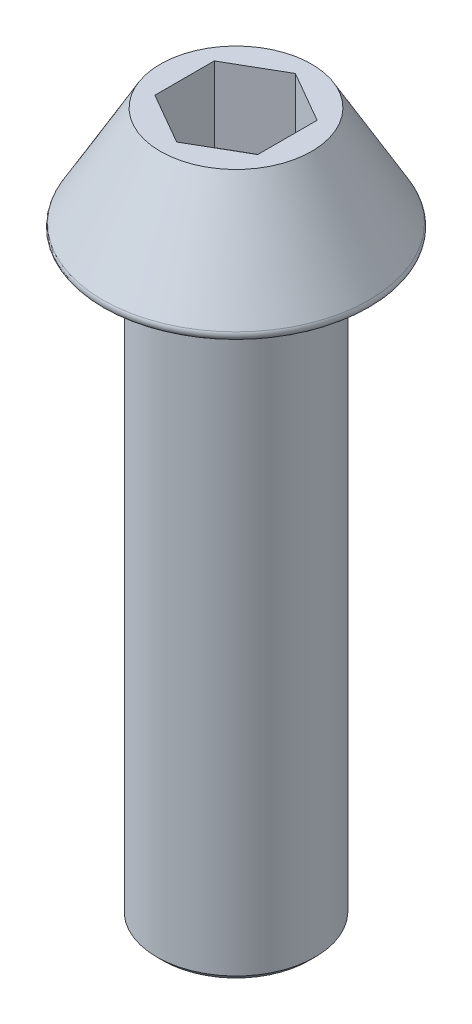
SolidWorks part; units mm, degrees
material "AISI 4340 Steel, annealed"
ref_plane "Front Plane" through (0, 0, 0) normal (0, 0, 1) x (1, 0, 0)
ref_plane "Top Plane" through (0, 0, 0) normal (0, 1, 0) x (1, 0, 0)
ref_plane "Right Plane" through (0, 0, 0) normal (1, 0, 0) x (0, 0, -1)
sketch "Sketch1" plane through (0, 0, 0) normal (0, 1, 0) x (1, 0, 0)
  circle A0 centre (0, 0) radius 4
  dimension "D1" = 8
extrude "Boss-Extrude1" add sketch "Sketch1" along normal blind 30
sketch "Sketch2" plane through (0, 30, 0) normal (0, 1, 0) x (1, 0, 0)
  circle A0 centre (0, 0) radius 7
  dimension "D1" = 14
extrude "Boss-Extrude2" add sketch "Sketch2" along normal blind 5.5 draft 30
sketch "Sketch3" plane through (0, 35.5, 0) normal (0, 1, 0) x (1, 0, 0)
  line L1 (0, 3.0022) -> (-2.6, 1.5011)
  line L2 (-2.6, 1.5011) -> (-2.6, -1.5011)
  line L3 (-2.6, -1.5011) -> (0, -3.0022)
  line L4 (0, -3.0022) -> (2.6, -1.5011)
  line L5 (2.6, -1.5011) -> (2.6, 1.5011)
  line L6 (2.6, 1.5011) -> (0, 3.0022)
  circle A0 centre (0, 0) radius 2.6 construction
  dimension "D1" = 5.2
extrude "Cut-Extrude1" cut sketch "Sketch3" against normal blind 3.8
sketch "Sketch4" plane through (0, 0, 0) normal (0, -1, 0) x (1, 0, 0)
  circle A0 centre (0, 0) radius 2.65
  dimension "D1" = 5.3
extrude "Cut-Extrude2" cut sketch "Sketch4" against normal blind 22
cosmetic thread "Cosmetic Thread1" parameters "D1"=15, "D2"=6
chamfer "Chamfer1" distance 0.3 angle 45 1 edges at (0, 0, 4)
fillet "Fillet1" radius 0.3 1 edges at (0, 30, 7)
